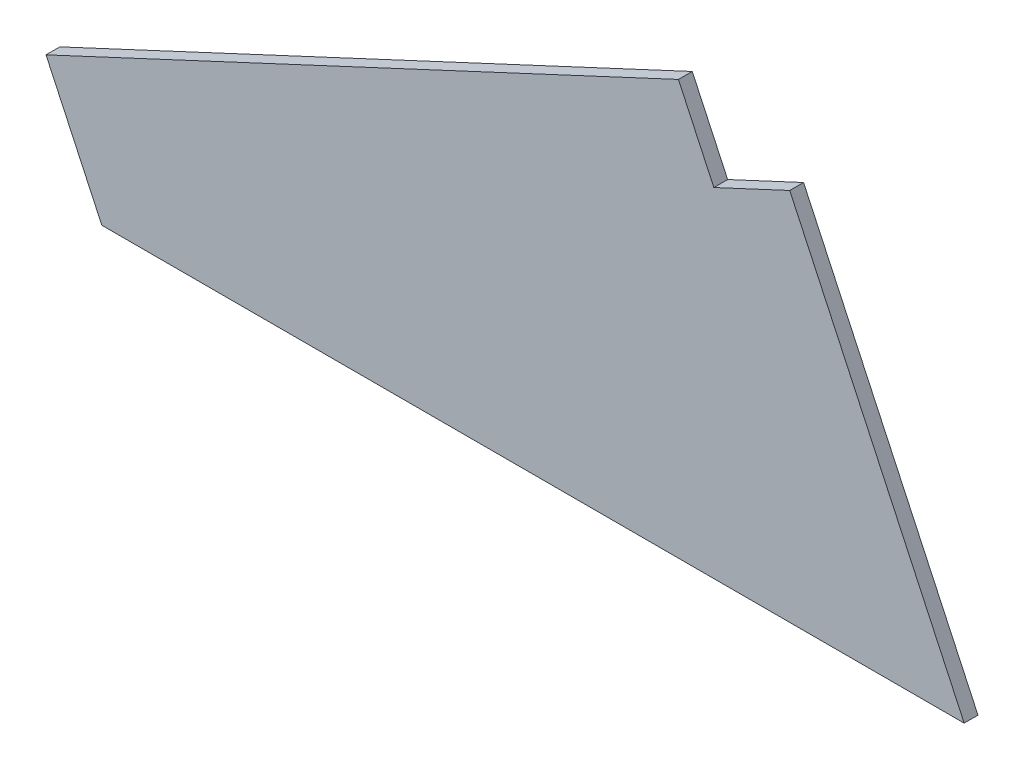
SolidWorks part; units mm, degrees
ref_plane "Front Plane" through (0, 0, 0) normal (0, 0, 1) x (1, 0, 0)
ref_plane "Top Plane" through (0, 0, 0) normal (0, 1, 0) x (1, 0, 0)
ref_plane "Right Plane" through (0, 0, 0) normal (1, 0, 0) x (0, 0, -1)
sketch "Sketch1" plane through (0, 0, 0) normal (0, 0, 1) x (1, 0, 0)
  line L0 (327.4362, 0.0035) -> (121.4984, 0.0035)
  line L1 (121.4984, 0.0035) -> (108.169, 28.5884)
  line L2 (108.169, 28.5884) -> (259.1989, 99.0148)
  line L3 (-63.4467, -51.4373) -> (255.5737, 97.3243) construction
  line L4 (259.1989, 99.0148) -> (267.6513, 80.8887)
  line L5 (267.6513, 80.8887) -> (285.7774, 89.341)
  line L6 (285.7774, 89.341) -> (327.4362, 0.0035)
  line L7 (327.4362, 0.0035) -> (398.701, -152.8244) construction
  dimension "D1" = 20
  dimension "D2" = 20
extrude "Boss-Extrude1" add sketch "Sketch1" against normal blind 3.3
